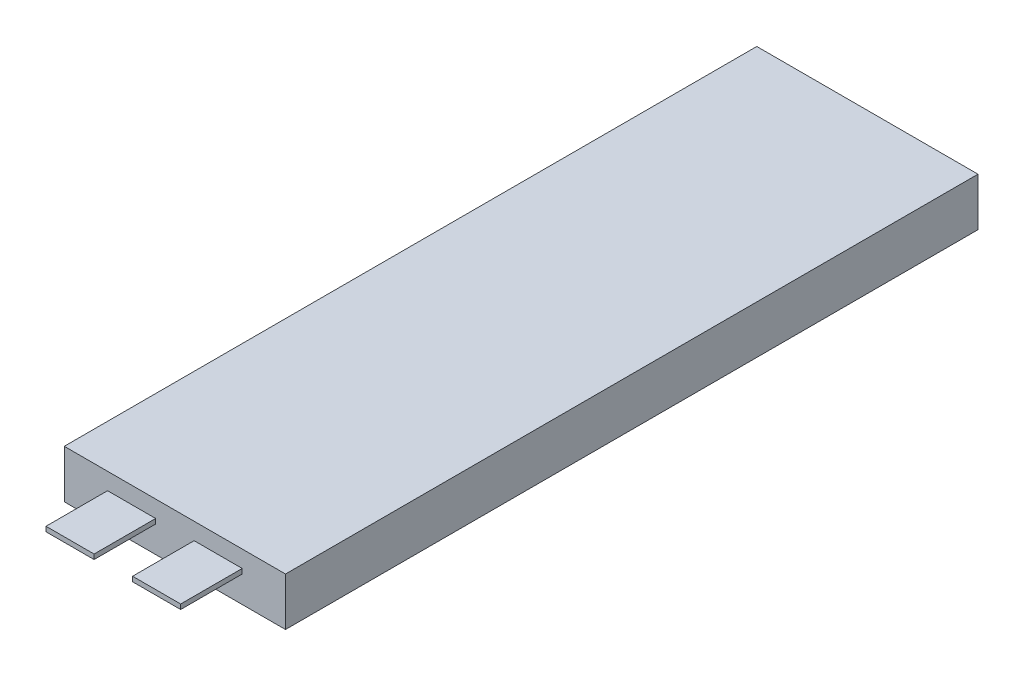
SolidWorks part; units mm, degrees
ref_plane "Front Plane" through (0, 0, 0) normal (0, 0, 1) x (1, 0, 0)
ref_plane "Top Plane" through (0, 0, 0) normal (0, 1, 0) x (1, 0, 0)
ref_plane "Right Plane" through (0, 0, 0) normal (1, 0, 0) x (0, 0, -1)
sketch "Sketch1" plane through (0, 0, 0) normal (0, 1, 0) x (1, 0, 0)
  line L2 (-23, 72) -> (23, 72)
  line L5 (-19, 72) -> (-19, 90)
  line L6 (-19, 90) -> (-4, 90)
  line L7 (-4, 90) -> (-4, 72)
  line L8 (4, 72) -> (4, 90)
  line L9 (4, 90) -> (19, 90)
  line L10 (19, 90) -> (19, 72)
  line L11 (0, 72) -> (0, 180.6197) construction
  line L13 (23, -72) -> (-23, -72)
  line L14 (23, -72) -> (23, 72)
  line L16 (-23, -72) -> (-23, 72)
  line L17 (23, -72) -> (-23, 72) construction
  line L18 (23, 72) -> (-23, -72) construction
  point P0 (0, 0)
  point P16 (-11.5, 90)
  point P17 (11.5, 90)
  dimension "D1" = 144
  dimension "D2" = 46
  dimension "D3" = 15
  dimension "D4" = 23
  dimension "D5" = 18
extrude "cell" add sketch "Sketch1" along normal blind 10 contours L2 L14 L13 L16
sketch "Sketch2" plane through (0, 0, 72) normal (0, 0, 1) x (1, 0, 0)
  line L1 (-14, 5.5) -> (-4, 5.5)
  line L2 (-14, 5.5) -> (-14, 6.5)
  line L3 (-14, 6.5) -> (-4, 6.5)
  line L4 (-4, 5.5) -> (-4, 6.5)
  line L5 (0, 0) -> (0, 10) construction
  line L6 (23, 10) -> (-23, 10) construction
  line L7 (4, 5.5) -> (4, 6.5)
  line L8 (14, 6.5) -> (4, 6.5)
  line L9 (14, 5.5) -> (14, 6.5)
  line L10 (14, 5.5) -> (4, 5.5)
  line L11 (23, 0) -> (-23, 0) construction
  point P4 (-3.5556, 1.8711)
  point P16 (-14, 6)
  dimension "D1" = 1
  dimension "D2" = 10
  dimension "D3" = 4
  dimension "D4" = 6
extrude "Boss-Extrude1" add sketch "Sketch2" along normal blind 12.8
equation "\"D1@cell\" = 10.00mm"
